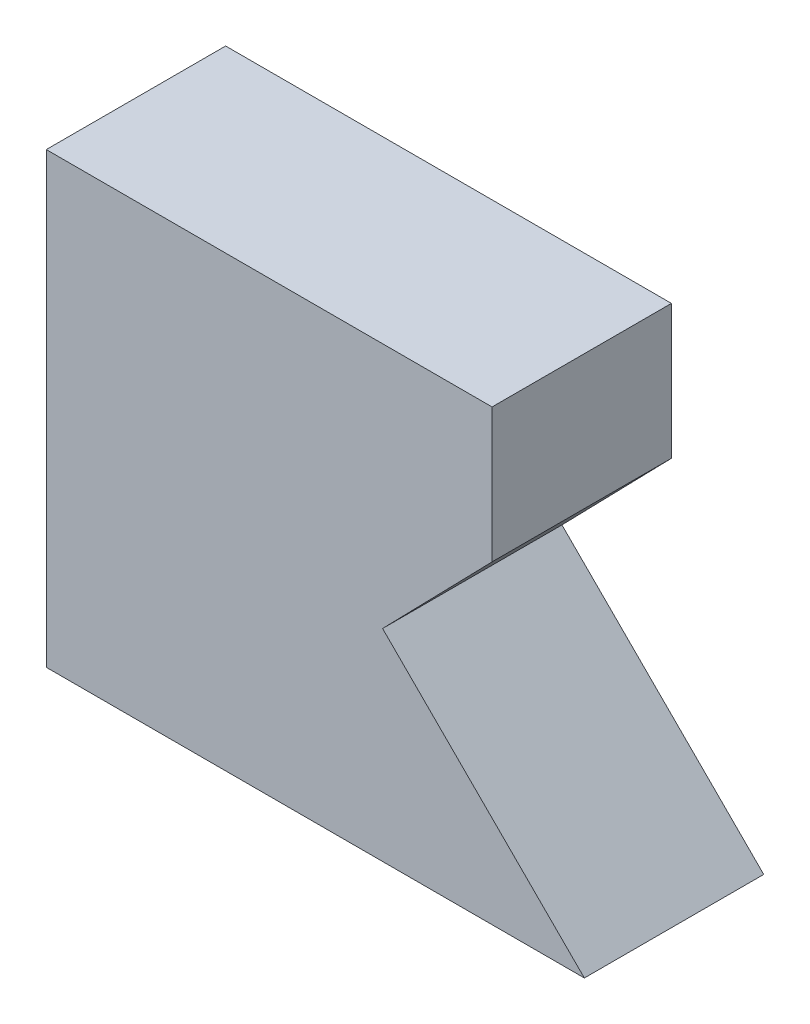
SolidWorks part; units mm, degrees
ref_plane "Plan de face" through (0, 0, 0) normal (0, 0, 1) x (1, 0, 0)
ref_plane "Plan de dessus" through (0, 0, 0) normal (0, 1, 0) x (1, 0, 0)
ref_plane "Plan de droite" through (0, 0, 0) normal (1, 0, 0) x (0, 0, -1)
sketch "Esquisse1" plane through (0, 0, 0) normal (0, 0, 1) x (1, 0, 0)
  line L0 (-60, 0) -> (60, 0)
  line L1 (-60, 0) -> (-60, 100)
  line L2 (60, 0) -> (15, 45)
  line L3 (15, 45) -> (39.4167, 70.0764)
  line L4 (39.4167, 70.0764) -> (39.4167, 100)
  line L5 (39.4167, 100) -> (-60, 100)
  point P4 (0, 0)
  point P10 (0, 0)
  point P11 (0, 0)
  dimension "D1" = 120
  dimension "D2" = 100
  dimension "D3" = 75
  dimension "D4" = 35
  dimension "D5" = 45
  dimension "D6" = 99.4167
extrude "Boss.-Extru.1" add sketch "Esquisse1" along normal blind 40
